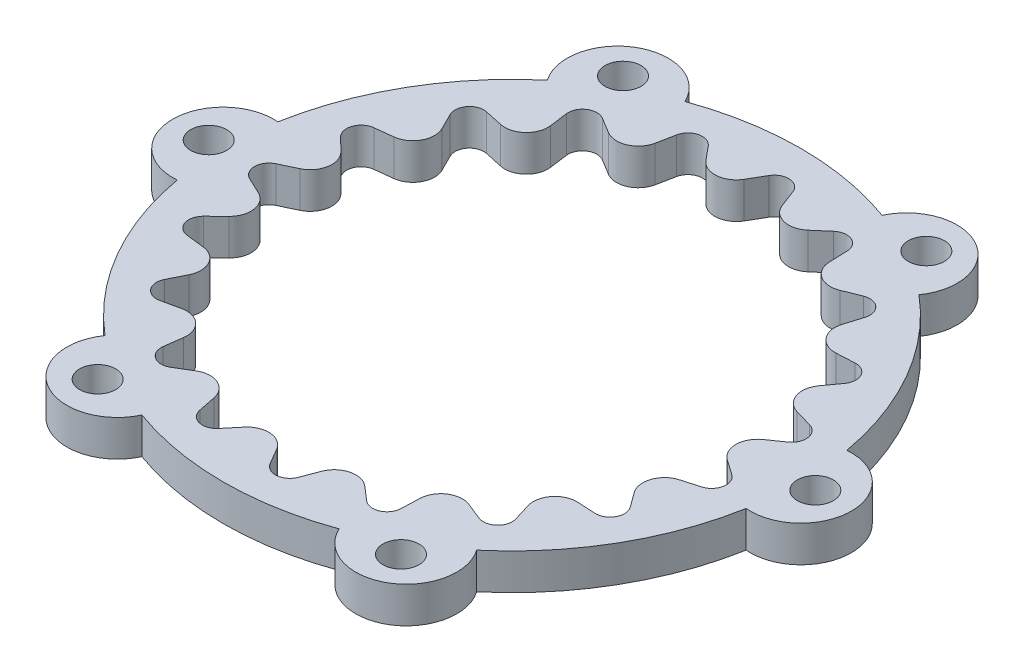
SolidWorks part; units mm, degrees
ref_plane "Front Plane" through (0, 0, 0) normal (0, 0, 1) x (1, 0, 0)
ref_plane "Top Plane" through (0, 0, 0) normal (0, 1, 0) x (1, 0, 0)
ref_plane "Right Plane" through (0, 0, 0) normal (1, 0, 0) x (0, 0, -1)
sketch "Sketch1" plane through (0, 0, 0) normal (0, 1, 0) x (1, 0, 0)
  line L6 (0, 0) -> (50.8, 0) construction
  line L11 (40.9947, -3.121) -> (43.18, 0) construction
  line L12 (43.18, 0) -> (40.9947, 3.121) construction
  line L14 (40.9947, 3.121) -> (49.9273, 9.3757)
  line L15 (49.9273, -9.3757) -> (40.9947, -3.121)
  circle A2 centre (0, 0) radius 50.8 construction
  arc A3 (40.9947, -3.121) -> (40.9947, 3.121) centre (43.18, 0) cw
  arc A4 (49.9273, 9.3757) -> (49.9273, -9.3757) centre (0, 0) cw
  dimension "D1" = 101.6
  dimension "D2" = 55
  dimension "D4" = 3.81
  dimension "D3" = 55
  dimension "D6" = 7.62
extrude "Boss-Extrude1" add sketch "Sketch1" along normal mid plane 6.35
pattern_circular "CirPattern4" count 19 over 360 about axis through (0, 0, 0) along (0, 1, 0) of "Boss-Extrude1"
fillet "Fillet1" radius 2.54 19 edges at (47.9693, 0, -8.0047) (47.9693, 0, 8.0047) (42.7711, 0, 23.1466) (32.938, 0, 35.7802) (19.5355, 0, 44.5364) (4.016, 0, 48.4665) (-11.9386, 0, 47.1445) (-26.5995, 0, 40.7136) (-38.378, 0, 29.8708) (-45.9975, 0, 15.791) (-48.6326, 0, 0) (-45.9975, 0, -15.791) (-38.378, 0, -29.8708) (-26.5995, 0, -40.7136) (-11.9386, 0, -47.1445) (4.016, 0, -48.4665) (32.938, 0, -35.7802) (42.7711, 0, -23.1466) (19.5355, 0, -44.5364)
sketch "Sketch5" plane through (0, 3.175, 0) normal (0, 1, 0) x (1, 0, 0)
  line L0 (0, 0) -> (50.8, 0) construction
  line L3 (50.0221, -8.8559) -> (45.72, 0)
  line L4 (45.72, 0) -> (50.0221, 8.8559)
  circle A0 centre (0, 0) radius 50.8 construction
  arc A1 (50.0221, 8.8559) -> (50.0221, -8.8559) centre (50.8, 0) cw
  dimension "D1" = 8.89
  dimension "D3" = 5.08
extrude "Boss-Extrude2" add sketch "Sketch5" against normal blind 6.35
sketch "Sketch7" plane through (0, 3.175, 0) normal (0, 1, 0) x (1, 0, 0)
  line L0 (53.34, 0) -> (59.69, 0) construction
  circle A0 centre (53.34, 0) radius 3.175
  arc A3 (50.0221, -8.8559) -> (50.0221, 8.8559) centre (50.8, 0) ccw construction
  dimension "D1" = 6.35
extrude "Cut-Extrude3" cut sketch "Sketch7" against normal blind 6.35
pattern_circular "CirPattern5" count 6 over 360 about axis through (0, 0, 0) along (0, 1, 0) of "Boss-Extrude2", "Cut-Extrude3"
equation "\"bore diamater\"= 0.25in"
equation "\"outer diameter\"= 0.5in"
